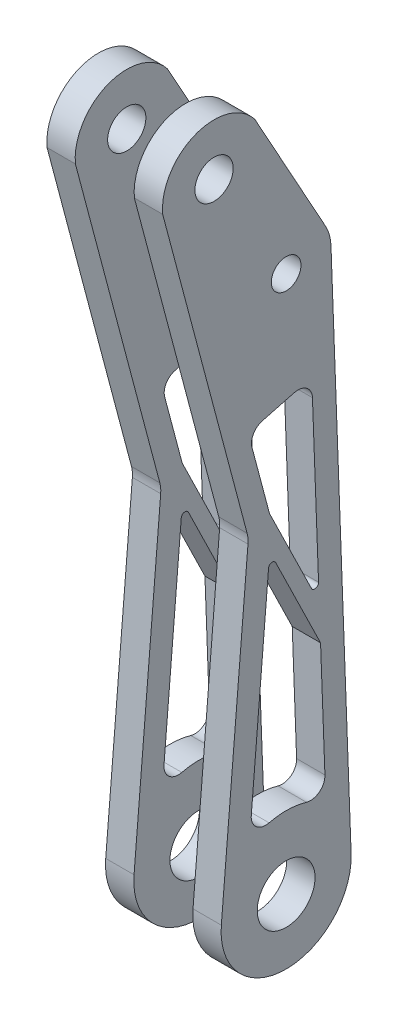
SolidWorks part; units mm, degrees
material "6061-T6 (SS)"
ref_plane "X-Y Datum" through (0, 0, 0) normal (0, 0, 1) x (1, 0, 0)
ref_plane "X-Z Datum" through (0, 0, 0) normal (0, 1, 0) x (1, 0, 0)
ref_plane "Y-Z Datum" through (0, 0, 0) normal (1, 0, 0) x (0, 0, -1)
sketch "Sketch6" plane through (0, 0, 0) normal (1, 0, 0) x (0, 0, -1)
  line L0 (0, 0) -> (0, 95.25) construction
  line L1 (0, 0) -> (0, 118.022) construction
  line L20 (-8.3819, 70.7797) -> (-14.2372, 1.1981)
  line L21 (9.8547, 118.3918) -> (11.5534, 73.1262)
  line L22 (-8.5717, 72.9399) -> (-27.1241, 142.8972)
  line L23 (11.5534, 73.1262) -> (14.2775, 0.5358)
  line L24 (-6.91, 150.8965) -> (8.7361, 122.5972)
  arc A0 (-14.2372, 1.1981) -> (14.2775, 0.5358) centre (0, 0) ccw
  arc A2 (8.7361, 122.5972) -> (9.8547, 118.3918) centre (0, 118.022) cw
  arc A4 (-8.3819, 70.7797) -> (-8.5717, 72.9399) centre (-14.7095, 71.3122) ccw
  circle A7 centre (0, 118.022) radius 3.2639
  arc A11 (-27.1241, 142.8972) -> (-6.91, 150.8965) centre (-15.8374, 143.9158) cw
  circle A12 centre (-15.8374, 143.9158) radius 4.1999
  point P8 (0, 82.55)
  point P12 (0, 82.55)
  point P14 (21.1318, 6.4606)
  point P18 (0, 63.5)
  point P20 (0, 101.6)
  point P25 (11.5534, 73.1262)
  dimension "D7" = 6.35
  dimension "D8" = 69.5816
  dimension "D3" = 6.5278
  dimension "D4" = 8.3998
  dimension "D10" = 72.5904
  dimension "D11" = 173.041
  dimension "D1" = 14.2875
  dimension "D6" = 117.856
  dimension "D9" = 4.81
  dimension "D14" = 25.493
  dimension "D15" = 63.5
  dimension "D16" = 82.55
  dimension "D17" = 101.6
extrude "Boss-Extrude3" add sketch "Sketch6" along normal mid plane 25.4
sketch "Sketch7" plane through (12.7, 0, 0) normal (1, 0, 0) x (0, 0, -1)
  circle A0 centre (0, 0) radius 6.35
  dimension "D1" = 12.7
extrude "Cut-Extrude1" cut sketch "Sketch7" against normal blind 7.1437 contours A0
sketch "Sketch8" plane through (5.5562, 0, 0) normal (1, 0, 0) x (0, 0, -1)
  circle A0 centre (0, 0) radius 7.9375
  dimension "D1" = 15.875
extrude "Cut-Extrude2" cut sketch "Sketch8" against normal blind 5.5562 contours A0
mirror "Mirror1" about plane through (0, 0, 0) normal (1, 0, 0) of "Cut-Extrude2"
mirror "Mirror2" about plane through (0, 0, 0) normal (1, 0, 0) of "Cut-Extrude1"
fillet "Fillet1" [suppressed] radius 1.5875
ref_plane "Plane1" through (0, 0, 14.2372) normal (0, 0, -1) x (-1, 0, 0)
sketch "Sketch10" plane through (0, 0, 14.2372) normal (0, 0, -1) x (-1, 0, 0)
  line L0 (-6.477, 155.9765) -> (-6.477, -18.6485)
  line L2 (-12.7, 150.8965) -> (12.7, 150.8965) construction
  line L4 (6.477, -18.6485) -> (6.477, 155.9765)
  line L5 (-6.477, 155.9765) -> (6.477, 155.9765)
  line L6 (-3.302, -21.8235) -> (3.302, -21.8235)
  arc A1 (3.302, -21.8235) -> (6.477, -18.6485) centre (3.302, -18.6485) ccw
  arc A2 (-3.302, -21.8235) -> (-6.477, -18.6485) centre (-3.302, -18.6485) cw
  point P9 (0, 155.9765)
  dimension "D3" = 177.8
  dimension "D1" = 12.954
  dimension "D2" = 5.08
extrude "Cut-Extrude3" cut sketch "Sketch10" along normal mid plane 58.42
sketch "Sketch11" [suppressed] plane through (-12.7, 0, 0) normal (-1, 0, 0) x (0, 0, 1)
  line L0 (-10.7679, 9.3907) -> (-8.2566, 76.313)
  line L1 (10.3203, 9.8805) -> (4.73, 76.313)
  line L2 (7.8475, 77.1297) -> (14.2372, 1.1981) construction
  line L4 (-14.2775, 0.5358) -> (-9.5183, 127.3572) construction
  arc A0 (10.3203, 9.8805) -> (-10.7679, 9.3907) centre (0, 0) ccw
  arc A1 (-8.2566, 76.313) -> (4.73, 76.313) centre (-1.7633, 89.0398) ccw
  dimension "D1" = 28.575
  dimension "D2" = 28.575
  dimension "D3" = 3.175
  dimension "D4" = 3.175
extrude "Cut-Extrude4" [suppressed] cut sketch "Sketch11" against normal blind 4.7625 contours A1 L1 A0 L0
mirror "Mirror3" [suppressed] about plane through (0, 0, 0) normal (1, 0, 0)
sketch "Sketch12" [suppressed] plane through (0, 0, 0) normal (1, 0, 0) x (0, 0, -1)
  line L0 (0, 95.25) -> (0, 120.65) construction
  line L1 (0, 120.65) -> (24.4512, 127.5273) construction
  line L2 (0, 95.25) -> (-24.8767, 90.1209) construction
  line L3 (0, 127) -> (326.3698, 134.0383) construction
  line L4 (0, 95.25) -> (0, 69.85) construction
  dimension "D1" = 50.8
  dimension "D2" = 78.35
  dimension "D3" = 25.4
  dimension "D4" = 25.4
sketch "Sketch13" plane through (12.7, 0, 0) normal (1, 0, 0) x (0, 0, -1)
  line L0 (-3.6614, 74.2421) -> (-8.3235, 91.8218)
  line L2 (-8.3235, 91.8218) -> (5.6294, 95.522)
  line L9 (-3.3198, 70.3537) -> (-8.0907, 13.6586)
  line L10 (5.6294, 95.522) -> (8.7161, 13.2682)
  line L12 (-8.3819, 70.7797) -> (-14.2372, 1.1981) construction
  line L13 (14.2775, 0.5358) -> (9.8547, 118.3918) construction
  arc A1 (8.7161, 13.2682) -> (-8.0907, 13.6586) centre (0, 0) ccw
  arc A2 (-3.6614, 74.2421) -> (-3.3198, 70.3537) centre (-14.7095, 71.3122) cw
  dimension "D3" = 15.875
  dimension "D4" = 11.43
  dimension "D2" = 18.1874
  dimension "D5" = 19.663
  dimension "D6" = 5.08
  dimension "D7" = 5.08
  dimension "D1" = 14.4352
extrude "Cut-Extrude5" cut sketch "Sketch13" against normal blind 25.4 contours L2 L10 A1 L9 A2 L0
fillet "Fillet2" radius 3.175 4 edges at (-9.5885, 91.8218, 8.3235) (-9.5885, 95.522, -5.6294) (-9.5885, 13.2682, -8.7161) (-9.5885, 13.6586, 8.0907)
fillet "Fillet3" radius 3.175 4 edges at (9.5885, 91.8218, 8.3235) (9.5885, 13.2682, -8.7161) (9.5885, 13.6586, 8.0907) (9.5885, 95.522, -5.6294)
sketch "Sketch21" plane through (12.7, 0, 0) normal (1, 0, 0) x (0, 0, -1)
  line L0 (-3.6614, 74.2421) -> (7.2678, 51.8613)
  line L1 (5.7783, 91.5544) -> (8.5234, 18.4022) construction
  line L2 (-3.6102, 66.9017) -> (7.5619, 44.0234)
  line L3 (-3.3198, 70.3537) -> (-7.6599, 18.7781) construction
  line L4 (7.5619, 44.0234) -> (7.2678, 51.8613)
  line L5 (-3.6102, 66.9017) -> (-3.3198, 70.3537)
  arc A0 (-3.3198, 70.3537) -> (-3.6614, 74.2421) centre (-14.7095, 71.3122) ccw
  dimension "D1" = 3.175
  dimension "D2" = 210.838
extrude "Boss-Extrude4" add sketch "Sketch21" against normal up to surface (6.223 mm away) up to face at (6.477, 57.9823, 1.0563)
fillet "Fillet4" radius 0.8255 2 edges at (9.5885, 66.9017, 3.6102) (9.5885, 51.8613, -7.2678)
sketch "Sketch23" plane through (-12.7, 0, -12.7) normal (1, 0, 0) x (0, 0, -1)
  line L0 (-16.3614, 74.2421) -> (-5.4322, 51.8613)
  line L2 (-16.3102, 66.9017) -> (-5.1381, 44.0234)
  line L4 (-5.1381, 44.0234) -> (-5.4322, 51.8613)
  line L5 (-16.3102, 66.9017) -> (-16.0198, 70.3537)
  line L6 (-6.9217, 91.5544) -> (-4.1766, 18.4022) construction
  arc A0 (-16.0198, 70.3537) -> (-16.3614, 74.2421) centre (-27.4095, 71.3122) ccw
  arc A1 (-16.0198, 70.3537) -> (-16.3614, 74.2421) centre (-27.4095, 71.3122) ccw construction
  dimension "D1" = 3.175
  dimension "D2" = 210.838
extrude "Boss-Extrude5" add sketch "Sketch23" along normal up to surface (6.223 mm away) up to face at (-6.477, 57.9823, 1.0563)
fillet "Fillet6" radius 0.8255 2 edges at (-9.5885, 51.8613, -7.2678) (-9.5885, 66.9017, 3.6102)
ref_plane "Plane2" through (25.4, 0, 0) normal (1, 0, 0) x (0, 0, -1)
sketch "Sketch17" plane through (-12.7, 0, 0) normal (-1, 0, 0) x (0, 0, 1)
  line L1 (-15.7464, -15.0456) -> (16.41, -15.0456)
  line L2 (-15.7464, -15.0456) -> (-15.7464, 137.8624)
  line L3 (-15.7464, 137.8624) -> (16.41, 137.8624)
  line L4 (16.41, -15.0456) -> (16.41, 137.8624)
  arc A0 (-14.2775, 0.5358) -> (14.2372, 1.1981) centre (0, 0) ccw construction
  point P8 (0.3318, -14.2836)
  point P9 (0.3318, -15.0456)
  dimension "D1" = 152.908
  dimension "D2" = 32.1564
  dimension "D3" = 0.762
sketch "Sketch18" plane through (25.4, 0, 0) normal (1, 0, 0) x (0, 0, -1)
  point P0 (0, 0)
sketch3d "3DSketch1"
  line L0 (12.7, 0, 0) -> (-12.7, 0, 0) construction
  line L1 (6.477, 0, 0) -> (12.7, 0, 0) construction
  line L2 (12.7, 0, 0) -> (6.477, 0, 0) construction
  line L4 (-6.477, 0, 0) -> (-12.7, 0, 0) construction
  point P10 (0, 0, 0)
sketch3d "3DSketch2"
  line L0 (12.7, 143.9158, 15.8374) -> (-12.7, 143.9158, 15.8374) construction
  line L3 (12.7, 118.022, 0) -> (-12.7, 118.022, 0) construction
  line L4 (12.7, 118.022, 0) -> (6.477, 118.022, 0) construction
  line L5 (-6.477, 118.022, 0) -> (-12.7, 118.022, 0) construction
  circle A0 centre (-12.7, 143.9158, 15.8374) radius 4.1999 construction
  point P5 (-8.5001, 143.9158, 15.8374)
  point P6 (0, 143.9158, 15.8374)
  point P13 (0, 118.022, 0)
sketch "Sketch19" plane through (0, 0, 0) normal (0, 0, 1) x (1, 0, 0)
  line L0 (0, 0) -> (0, -38.1) construction
  dimension "D1" = 38.1
